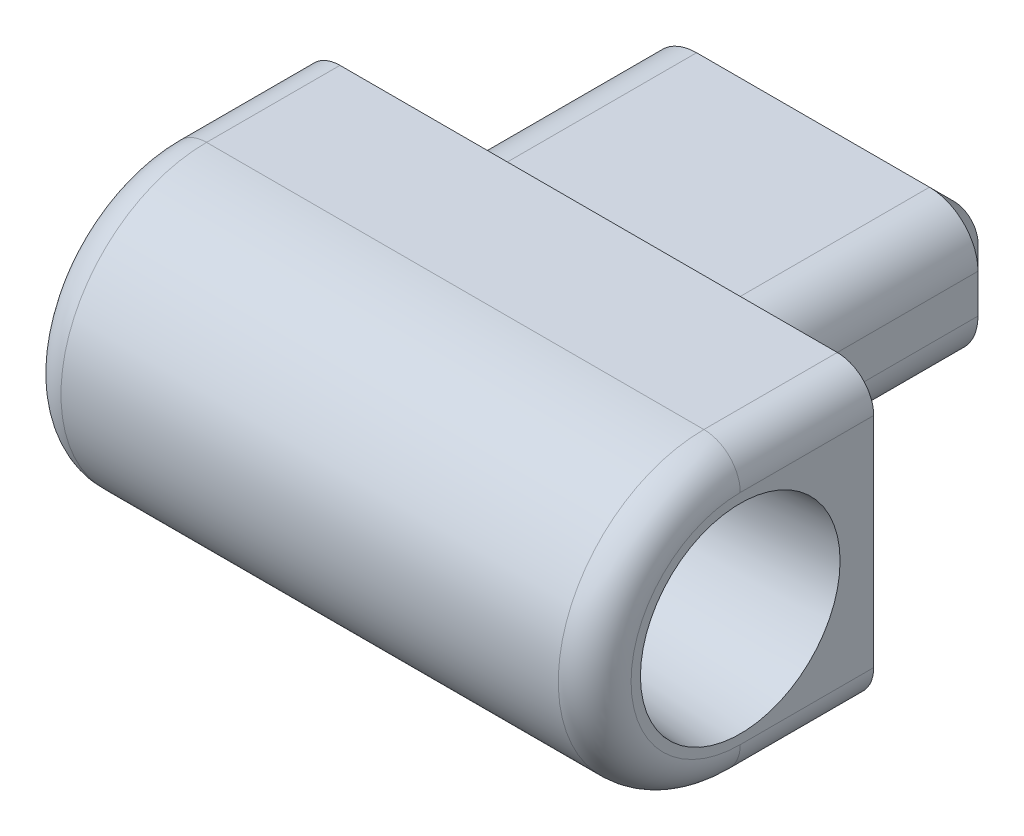
SolidWorks part; units mm, degrees
ref_plane "Front Plane" through (0, 0, 0) normal (0, 0, 1) x (1, 0, 0)
ref_plane "Top Plane" through (0, 0, 0) normal (0, 1, 0) x (1, 0, 0)
ref_plane "Right Plane" through (0, 0, 0) normal (1, 0, 0) x (0, 0, -1)
ref_plane "Plane1" through (-29.5, 0, 0) normal (-1, 0, 0) x (0, 0, 1)
sketch "Sketch2" plane through (-29.5, 0, 0) normal (-1, 0, 0) x (0, 0, 1)
  line L0 (2.75, -3) -> (0, -3)
  line L1 (0, 45) -> (0, -54.2) construction
  line L2 (0, -3) -> (0, 3)
  line L3 (0, 0) -> (5.75, 0) construction
  line L4 (5.75, 3.099) -> (5.75, -2.6607) construction
  line L10 (0, 3) -> (2.75, 3)
  arc A0 (2.75, 3) -> (2.75, -3) centre (2.75, 0) cw
  dimension "D1" = 2.75
  dimension "D2" = 6
extrude "body" add sketch "Sketch2" along normal blind 11.75 from offset 1.25
sketch "Sketch3" plane through (0, 0, 0) normal (0, 0, -1) x (-1, 0, 0)
  line L0 (34.1, 0) -> (40.9, 0) construction
  line L2 (35.1, 1.4) -> (39.9, 1.4)
  line L3 (34.1, 0.4) -> (34.1, -0.4)
  line L4 (35.1, -1.4) -> (39.9, -1.4)
  line L5 (40.9, 0.4) -> (40.9, -0.4)
  line L8 (41, 1.5) -> (41, -1.5) construction
  line L9 (34, 1.5) -> (41, 1.5) construction
  arc A0 (35.1, 1.4) -> (34.1, 0.4) centre (35.1, 0.4) ccw
  arc A1 (34.1, -0.4) -> (35.1, -1.4) centre (35.1, -0.4) ccw
  arc A2 (39.9, -1.4) -> (40.9, -0.4) centre (39.9, -0.4) ccw
  arc A3 (39.9, 1.4) -> (40.9, 0.4) centre (39.9, 0.4) cw
  point P3 (37.5, 0)
  point P8 (0, 0)
  point P14 (0, 0)
  point P15 (0, 0)
  point P16 (0, 0)
  dimension "D3" = 1
  dimension "D1" = 0.1
  dimension "D2" = 0.1
extrude "peg" add sketch "Sketch3" along normal blind 6
chamfer "Chamfer1" distance 0.5 angle 45 8 edges at (-37.5, 1.4, -6) (-40.6071, 1.1071, -6) (-40.9, 0, -6) (-40.6071, -1.1071, -6) (-37.5, -1.4, -6) (-34.3929, -1.1071, -6) (-34.1, 0, -6) (-34.3929, 1.1071, -6)
hole_wizard "9/64 (0.14063) Diameter Hole1" positions "Sketch4" profile "Sketch5" hole size "9/64" standard "ANSI Inch"
sketch "Sketch4" plane through (-30.75, 0, 0) normal (1, 0, 0) x (0, 0, -1)
  arc A0 (-2.75, 3) -> (-2.75, -3) centre (-2.75, 0) ccw construction
  point P0 (-2.75, 0)
  point P3 (0, 0)
sketch "Sketch5" plane through (-30.75, 0, 2.75) normal (0, 1, 0) x (0, 0, -1)
  line L0 (0, 0) -> (0, 8.0731)
  line L1 (0, 8.0731) -> (1.786, 7)
  line L2 (1.786, 7) -> (1.786, 3.8812)
  line L3 (1.786, 3.8812) -> (2.0574, 0)
  line L5 (2.0574, 0) -> (0, 0)
  line L6 (-1.786, 3.8812) -> (-2.0574, 0) construction
  line L10 (0, 8.0731) -> (-1.786, 7) construction
  line L11 (0, -6.35) -> (0, 107.95) construction
  dimension "Hole Dia." = 3.572
  dimension "Hole Depth" = 7
  dimension "Near C'Sink Dia." = 4.1148
  dimension "Near C'Sink Angle" = 8
  dimension "Drill Angle" = 118
hole_wizard "M2.5 Clearance Hole1" positions "Sketch6" profile "Sketch7" hole size "M2.5" standard "ISO" end condition through all
sketch "Sketch6" plane through (-42.5, 0, 0) normal (-1, 0, 0) x (0, 0, 1)
  arc A1 (2.75, -3) -> (2.75, 3) centre (2.75, 0) ccw construction
  point P0 (2.75, 0)
  point P3 (0, 0)
  point P7 (0, 0)
  point P8 (0, 0)
sketch "Sketch7" plane through (-42.5, 0, 2.75) normal (0, 1, 0) x (0, 0, 1)
  line L0 (0, 0) -> (0, 11.75)
  line L1 (0, 11.75) -> (1.35, 11.75)
  line L2 (1.35, 11.75) -> (1.35, 0.025)
  line L3 (1.35, 0.025) -> (1.375, 0)
  line L5 (1.375, 0) -> (0, 0)
  line L6 (-1.35, 0.025) -> (-1.375, 0) construction
  line L11 (0, -6.35) -> (0, 107.95) construction
  dimension "Thru Hole Dia." = 2.7
  dimension "Thru Hole Depth" = 11.75
  dimension "Near C'Sink Dia." = 2.75
  dimension "Near C'Sink Angle" = 90
fillet "Fillet3" radius 0.75 6 edges at (-30.75, -3, 1.375) (-30.75, 3, 1.375) (-42.5, -3, 1.375) (-42.5, 3, 1.375) (-30.75, 0, 5.75) (-42.5, 0, 5.75)
